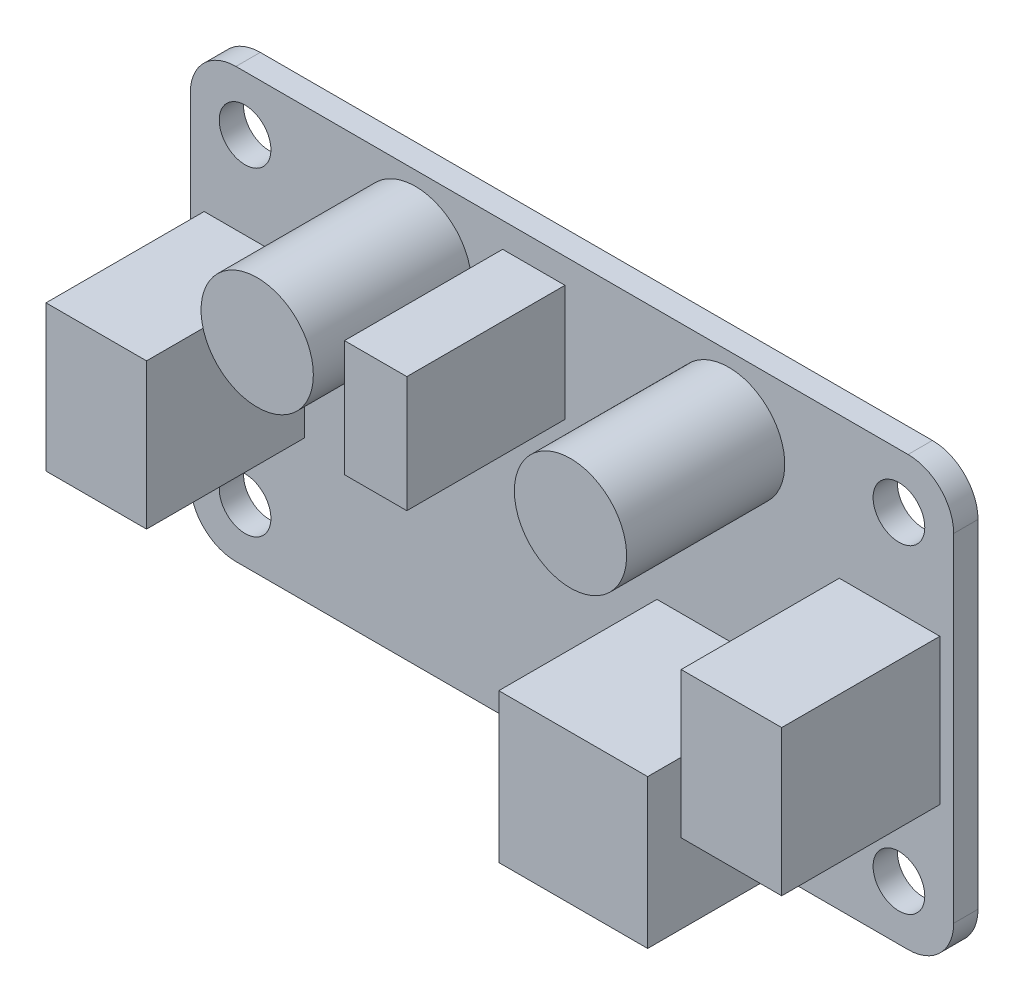
SolidWorks part; units mm, degrees
ref_plane "Plan de face" through (0, 0, 0) normal (0, 0, 1) x (1, 0, 0)
ref_plane "Plan de dessus" through (0, 0, 0) normal (0, 1, 0) x (1, 0, 0)
ref_plane "Plan de droite" through (0, 0, 0) normal (1, 0, 0) x (0, 0, -1)
sketch "Esquisse1" plane through (0, 0, 0) normal (0, 0, 1) x (1, 0, 0)
  line L1 (-25.1, 14.1) -> (25.1, 14.1)
  line L2 (-25.1, 14.1) -> (-25.1, -14.1)
  line L3 (-25.1, -14.1) -> (25.1, -14.1)
  line L4 (25.1, 14.1) -> (25.1, -14.1)
  point P4 (0, 14.1)
  point P6 (-25.1, 0)
  dimension "D1" = 50.2
  dimension "D2" = 28.2
extrude "Boss.-Extru.1" add sketch "Esquisse1" along normal blind 1.6
hole_wizard "Dégagement M31" positions "Esquisse3" profile "Esquisse4" hole size "M3" standard "ISO" end condition through all
sketch "Esquisse3" plane through (0, 0, 1.6) normal (0, 0, 1) x (1, 0, 0)
  line L0 (0, 0) -> (0, 5.8427) construction
  line L2 (0, 0) -> (4.0489, 0) construction
  point P0 (-21.5, 10.5)
  point P12 (21.5, 10.5)
  point P13 (21.5, -10.5)
  point P14 (-21.5, -10.5)
  dimension "D1" = 21
  dimension "D2" = 43
sketch "Esquisse4" plane through (-21.5, 10.5, 1.6) normal (1, 0, 0) x (0, -1, 0)
  line L0 (0, 0) -> (0, 1.6)
  line L1 (0, 1.6) -> (1.7, 1.6)
  line L2 (1.7, 1.6) -> (1.7, 0)
  line L5 (1.7, 0) -> (0, 0)
  line L11 (0, -6.35) -> (0, 107.95) construction
  dimension "Diamètre du perçage jusqu'au prochain" = 3.4
  dimension "Profondeur du perçage jusqu'au prochain" = 1.6
fillet "Congé1" radius 3 4 edges at (-25.1, 14.1, 0.8) (25.1, 14.1, 0.8) (25.1, -14.1, 0.8) (-25.1, -14.1, 0.8)
sketch "Esquisse5" plane through (0, 0, 1.6) normal (0, 0, 1) x (1, 0, 0)
  line L0 (0, 0) -> (0, 5.7402) construction
  line L1 (-24.1907, 4.792) -> (-17.5793, 4.792)
  line L2 (-24.1907, 4.792) -> (-24.1907, -4.792)
  line L3 (-24.1907, -4.792) -> (-17.5793, -4.792)
  line L4 (-17.5793, 4.792) -> (-17.5793, -4.792)
  line L9 (17.5793, 4.792) -> (17.5793, -4.792)
  line L10 (24.1907, -4.792) -> (17.5793, -4.792)
  line L11 (24.1907, 4.792) -> (24.1907, -4.792)
  line L12 (24.1907, 4.792) -> (17.5793, 4.792)
  line L14 (-4.5614, 12.4541) -> (-0.4613, 12.4541)
  line L15 (-4.5614, 12.4541) -> (-4.5614, 4.8176)
  line L16 (-4.5614, 4.8176) -> (-0.4613, 4.8176)
  line L17 (-0.4613, 12.4541) -> (-0.4613, 4.8176)
  line L18 (5.5864, -2.4088) -> (15.3755, -2.4088)
  line L19 (5.5864, -2.4088) -> (5.5864, -12.1979)
  line L20 (5.5864, -12.1979) -> (15.3755, -12.1979)
  line L21 (15.3755, -2.4088) -> (15.3755, -12.1979)
  circle A0 centre (-10.3016, 9.4815) radius 3.6919
  circle A2 centre (10.3016, 9.4815) radius 3.6919
  point P4 (-17.5793, 0)
extrude "Boss.-Extru.2" add sketch "Esquisse5" along normal blind 10.4
